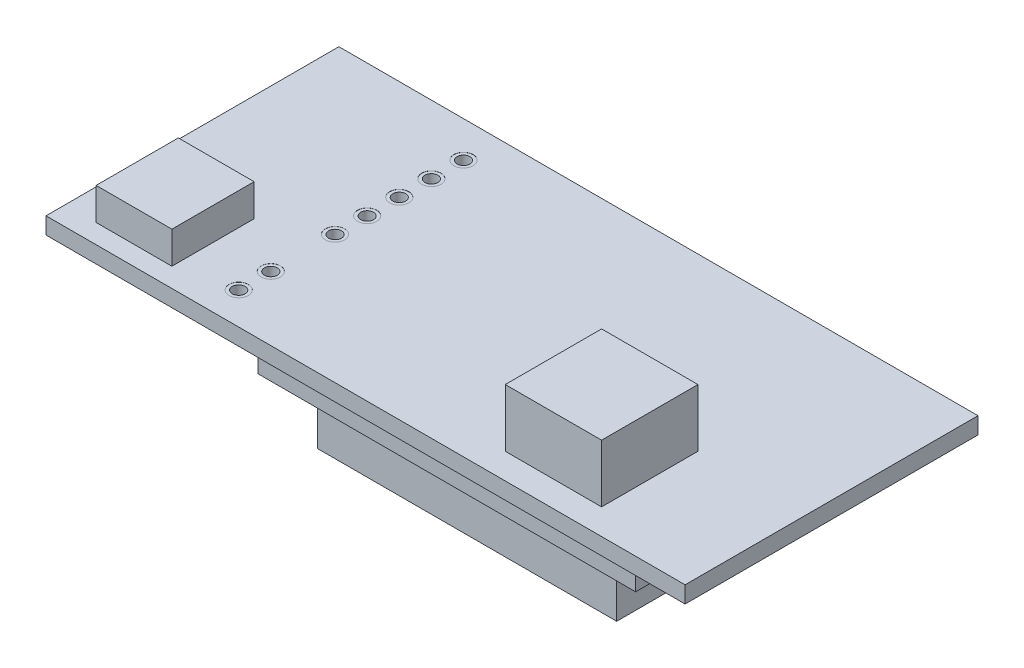
SolidWorks part; units mm, degrees
ref_plane "Front Plane" through (0, 0, 0) normal (0, 0, 1) x (1, 0, 0)
ref_plane "Top Plane" through (0, 0, 0) normal (0, 1, 0) x (1, 0, 0)
ref_plane "Right Plane" through (0, 0, 0) normal (1, 0, 0) x (0, 0, -1)
sketch "Sketch1" plane through (0, 0, 0) normal (0, 1, 0) x (1, 0, 0)
  line L1 (-24.875, 11.4) -> (24.875, 11.4)
  line L2 (-24.875, 11.4) -> (-24.875, -11.4)
  line L3 (-24.875, -11.4) -> (24.875, -11.4)
  line L4 (24.875, 11.4) -> (24.875, -11.4)
  line L5 (-24.875, 11.4) -> (24.875, -11.4) construction
  line L6 (-24.875, -11.4) -> (24.875, 11.4) construction
  point P0 (0, 0)
  dimension "D1" = 22.8
  dimension "D2" = 49.75
extrude "Boss-Extrude1" add sketch "Sketch1" along normal blind 1.3
sketch "Sketch2" plane through (0, 1.3, 0) normal (0, 1, 0) x (1, 0, 0)
  line L0 (24.875, -11.4) -> (24.875, 11.4) construction
  line L1 (8.875, -1.9) -> (16.375, -1.9)
  line L2 (8.875, -1.9) -> (8.875, -9.4)
  line L3 (8.875, -9.4) -> (16.375, -9.4)
  line L4 (16.375, -1.9) -> (16.375, -9.4)
  line L5 (-24.875, -11.4) -> (24.875, -11.4) construction
  dimension "D1" = 7.5
  dimension "D2" = 7.5
  dimension "D3" = 8.5
  dimension "D4" = 2
extrude "Boss-Extrude2" add sketch "Sketch2" along normal blind 4.5
sketch "Sketch3" plane through (0, 1.3, 0) normal (0, 1, 0) x (1, 0, 0)
  line L0 (-24.875, 11.4) -> (-24.875, -11.4) construction
  line L1 (-22.475, -3.5) -> (-16.575, -3.5)
  line L2 (-22.475, -3.5) -> (-22.475, -9.9)
  line L3 (-22.475, -9.9) -> (-16.575, -9.9)
  line L4 (-16.575, -3.5) -> (-16.575, -9.9)
  line L5 (-24.875, -11.4) -> (24.875, -11.4) construction
  dimension "D1" = 5.9
  dimension "D2" = 6.4
  dimension "D3" = 2.4
  dimension "D4" = 1.5
extrude "Boss-Extrude3" add sketch "Sketch3" along normal blind 2.5
sketch "Sketch4" plane through (0, 0, 0) normal (0, -1, 0) x (1, 0, 0)
  line L0 (24.875, 11.4) -> (24.875, -11.4) construction
  line L1 (20.175, 10.55) -> (-9.225, 10.55)
  line L2 (20.175, 10.55) -> (20.175, -10.55)
  line L3 (20.175, -10.55) -> (-9.225, -10.55)
  line L4 (-9.225, 10.55) -> (-9.225, -10.55)
  line L5 (-24.875, 0) -> (24.875, 0) construction
  line L6 (-24.875, -11.4) -> (-24.875, 11.4) construction
  line L7 (-9.225, 0) -> (20.175, 0) construction
  dimension "D1" = 21.1
  dimension "D2" = 29.4
  dimension "D3" = 4.7
extrude "Boss-Extrude4" add sketch "Sketch4" along normal blind 1.95
sketch "Sketch5" plane through (0, -1.95, 0) normal (0, -1, 0) x (1, 0, 0)
  line L0 (-9.225, 0) -> (20.175, 0) construction
  line L1 (-5.025, 10.125) -> (18.275, 10.125)
  line L2 (-5.025, 10.125) -> (-5.025, -10.125)
  line L3 (-5.025, -10.125) -> (18.275, -10.125)
  line L4 (18.275, 10.125) -> (18.275, -10.125)
  line L5 (-9.225, 10.55) -> (-9.225, -10.55) construction
  line L6 (20.175, -10.55) -> (20.175, 10.55) construction
  line L7 (-5.025, 0) -> (18.275, 0) construction
  dimension "D1" = 20.25
  dimension "D2" = 23.3
  dimension "D3" = 1.9
extrude "Boss-Extrude5" add sketch "Sketch5" along normal offset from surface (3.15 mm away) 10.9 up to face at (12.625, 5.8, 5.65)
sketch "Sketch6" plane through (0, 0, 0) normal (0, -1, 0) x (1, 0, 0)
  line L0 (-12.375, 11.4) -> (-12.375, -11.4) construction
  line L1 (-24.875, 11.4) -> (24.875, 11.4) construction
  line L2 (24.875, -11.4) -> (-24.875, -11.4) construction
  line L3 (-24.875, 8.9) -> (24.875, 8.9) construction
  line L4 (-24.875, -11.4) -> (-24.875, 11.4) construction
  line L5 (24.875, 11.4) -> (24.875, -11.4) construction
  circle A0 centre (-12.375, 8.9) radius 0.5
  circle A1 centre (-12.375, 6.4) radius 0.5
  circle A2 centre (-12.375, 3.9) radius 0.5 [skipped]
  circle A3 centre (-12.375, 1.4) radius 0.5
  circle A4 centre (-12.375, -1.1) radius 0.5
  circle A5 centre (-12.375, -3.6) radius 0.5
  circle A6 centre (-12.375, -6.1) radius 0.5
  circle A7 centre (-12.375, -8.6) radius 0.5
  dimension "D3" = 1
  dimension "D1" = 12.5
  dimension "D2" = 2.5
  dimension "D5" = 2.5
  dimension "D4" = 8
extrude "Cut-Extrude1" cut sketch "Sketch6" against normal up to next
sketch "Sketch7" plane through (0, 0, 0) normal (0, -1, 0) x (1, 0, 0)
  circle A0 centre (-12.375, 8.9) radius 0.75
  circle A1 centre (-12.375, 6.4) radius 0.75
  circle A2 centre (-12.375, 1.4) radius 0.75
  circle A3 centre (-12.375, -1.1) radius 0.75
  circle A4 centre (-12.375, -3.6) radius 0.75
  circle A5 centre (-12.375, -6.1) radius 0.75
  circle A6 centre (-12.375, -8.6) radius 0.75
  dimension "D1" = 1.5
extrude "Cut-Extrude2" cut sketch "Sketch7" against normal blind 0.01
sketch "Sketch8" plane through (0, 1.3, 0) normal (0, 1, 0) x (1, 0, 0)
  circle A0 centre (-12.375, 8.6) radius 0.75
  circle A1 centre (-12.375, 8.6) radius 0.75 construction
  circle A2 centre (-12.375, 6.1) radius 0.75
  circle A3 centre (-12.375, 3.6) radius 0.75
  circle A4 centre (-12.375, 1.1) radius 0.75
  circle A5 centre (-12.375, -1.4) radius 0.75
  circle A6 centre (-12.375, -6.4) radius 0.75
  circle A7 centre (-12.375, -8.9) radius 0.75
extrude "Cut-Extrude3" cut sketch "Sketch8" against normal blind 0.01
